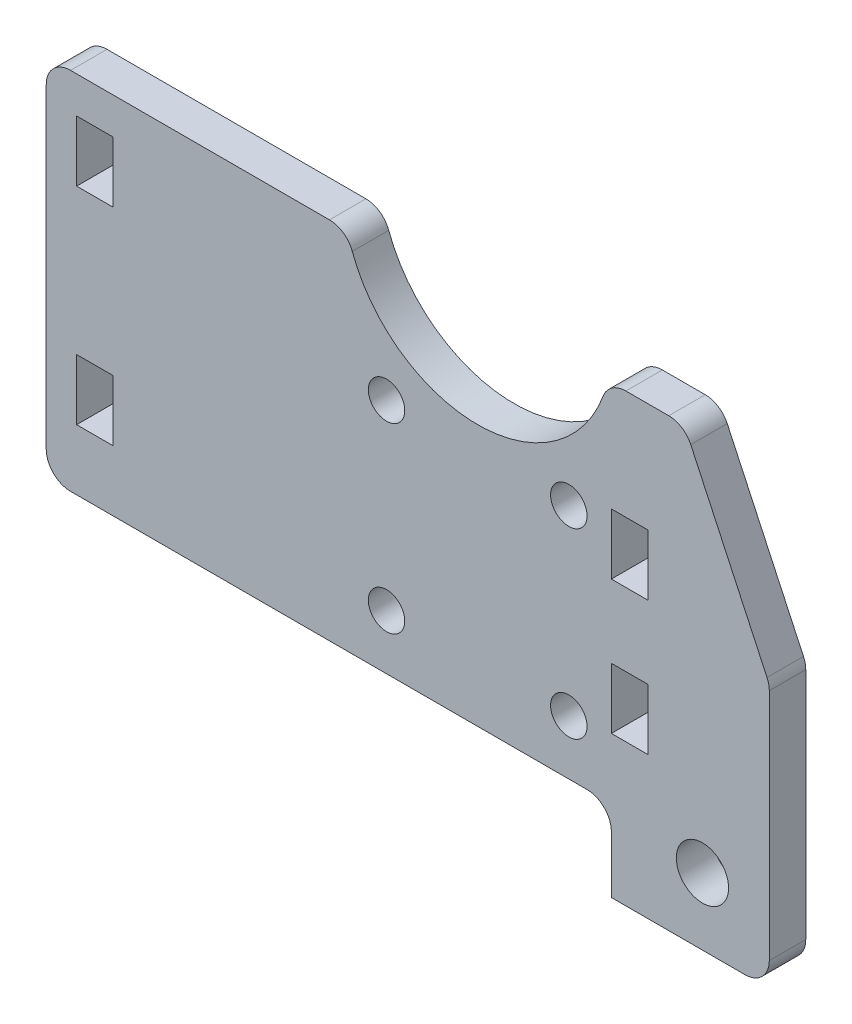
SolidWorks part; units mm, degrees
ref_plane "Front Plane" through (0, 0, 0) normal (0, 0, 1) x (1, 0, 0)
ref_plane "Top Plane" through (0, 0, 0) normal (0, 1, 0) x (1, 0, 0)
ref_plane "Right Plane" through (0, 0, 0) normal (1, 0, 0) x (0, 0, -1)
sketch "草图1" plane through (0, 0, 0) normal (0, 0, 1) x (1, 0, 0)
  line L1 (-26, -15) -> (26, -15)
  line L2 (-26, -15) -> (-26, 15)
  line L3 (-26, 15) -> (26, 15)
  line L4 (26, -15) -> (26, 15)
  line L5 (-26, -15) -> (26, 15) construction
  line L6 (-26, 15) -> (26, -15) construction
  point P0 (0, 0)
  dimension "D1" = 30
  dimension "D2" = 52
extrude "凸台-拉伸1" add sketch "草图1" along normal blind 3
sketch "草图2" plane through (0, 0, 3) normal (0, 0, 1) x (1, 0, 0)
  line L0 (0, 23.231) -> (0, -23.2713) construction
  line L1 (23.5, 27.0014) -> (23.5, -24.4496) construction
  line L2 (26, -15) -> (26, 15) construction
  line L3 (-29.6284, 0) -> (37.0615, 0) construction
  line L4 (-26, -15) -> (26, -15) construction
  line L5 (23.5, -5) -> (20.5, -5)
  line L6 (23.5, -5) -> (23.5, -10)
  line L7 (23.5, -10) -> (20.5, -10)
  line L8 (20.5, -5) -> (20.5, -10)
  line L9 (23.5, -5) -> (20.5, -10) construction
  line L10 (23.5, -10) -> (20.5, -5) construction
  line L11 (23.5, 12) -> (20.5, 12)
  line L12 (23.5, 12) -> (23.5, 7)
  line L13 (23.5, 7) -> (20.5, 7)
  line L14 (20.5, 12) -> (20.5, 7)
  line L15 (23.5, 12) -> (20.5, 7) construction
  line L16 (23.5, 7) -> (20.5, 12) construction
  line L17 (-23.5, 7) -> (-20.5, 12) construction
  line L18 (-23.5, 12) -> (-20.5, 7) construction
  line L19 (-23.5, -10) -> (-20.5, -5) construction
  line L20 (-23.5, -5) -> (-20.5, -10) construction
  line L21 (-20.5, 12) -> (-20.5, 7)
  line L22 (-23.5, 7) -> (-20.5, 7)
  line L23 (-23.5, 12) -> (-23.5, 7)
  line L24 (-23.5, 12) -> (-20.5, 12)
  line L25 (-20.5, -5) -> (-20.5, -10)
  line L26 (-23.5, -10) -> (-20.5, -10)
  line L27 (-23.5, -5) -> (-23.5, -10)
  line L28 (-23.5, -5) -> (-20.5, -5)
  point P13 (22, -7.5)
  point P18 (22, 9.5)
  point P29 (-22, 9.5)
  point P30 (-22, -7.5)
  dimension "D1" = 2.5
  dimension "D2" = 3
  dimension "D3" = 3
  dimension "D4" = 5
  dimension "D5" = 5
  dimension "D6" = 12
  dimension "D7" = 5
extrude "切除-拉伸1" cut sketch "草图2" against normal blind 4
sketch "草图6" plane through (0, 0, 0) normal (0, 0, -1) x (-1, 0, 0)
  line L1 (-24.1777, 12.7083) -> (-19.5538, 12.7083)
  line L2 (-24.1777, 12.7083) -> (-24.1777, 6.3305)
  line L3 (-24.1777, 6.3305) -> (-19.5538, 6.3305)
  line L4 (-19.5538, 12.7083) -> (-19.5538, 6.3305)
  line L5 (-24.1777, 12.7083) -> (-19.5538, 6.3305) construction
  line L6 (-24.1777, 6.3305) -> (-19.5538, 12.7083) construction
  point P4 (-21.8658, 9.5194)
extrude "凸台-拉伸2" add sketch "草图6" against normal up to surface (3 mm away) up to face at (-22, -7.5, 3)
sketch "草图7" plane through (0, 0, 0) normal (0, 0, -1) x (-1, 0, 0)
  line L1 (-23.5, 1) -> (-20.5, 1)
  line L2 (-23.5, 1) -> (-23.5, 6)
  line L3 (-23.5, 6) -> (-20.5, 6)
  line L4 (-20.5, 1) -> (-20.5, 6)
  line L5 (-23.5, 1) -> (-20.5, 6) construction
  line L6 (-23.5, 6) -> (-20.5, 1) construction
  line L7 (-23.5, -5) -> (-23.5, -10) construction
  line L8 (-20.5, -5) -> (-23.5, -5) construction
  point P4 (-22, 3.5)
  dimension "D1" = 3
  dimension "D2" = 5
  dimension "D3" = 6
extrude "切除-拉伸4" cut sketch "草图7" against normal blind 10
sketch "草图8" plane through (0, 0, 3) normal (0, 0, 1) x (1, 0, 0)
  line L0 (26, -15) -> (26, 15) construction
  line L1 (-26, -15) -> (26, -15) construction
  line L2 (26, 15) -> (31.495, 15)
  line L3 (31.495, 15) -> (31.495, -21.695)
  line L4 (31.495, -21.695) -> (20.5, -21.695)
  line L5 (20.5, -21.695) -> (20.5, -15)
  line L6 (20.5, -5) -> (20.5, -10) construction
  line L7 (26, 15) -> (26, -15)
  line L8 (26, -15) -> (20.5, -15)
  circle A0 centre (27.995, -16.195) radius 2
  dimension "D1" = 4
  dimension "D2" = 1.995
  dimension "D3" = 1.195
  dimension "D4" = 3.5
  dimension "5.5" = 5.5
extrude "凸台-拉伸3" add sketch "草图8" against normal up to surface (3 mm away) up to face at (22, 3.5, 0)
sketch "草图9" plane through (0, 0, 3) normal (0, 0, 1) x (1, 0, 0)
  circle A0 centre (27.995, -16.195) radius 2.25
  dimension "D1" = 4.5
extrude "切除-拉伸5" cut sketch "草图9" against normal blind 10
sketch "草图10" plane through (0, 0, 0) normal (0, 0, -1) x (-1, 0, 0)
  line L0 (-17, 4.5) -> (-2, 4.5) construction
  line L1 (-20.5, -10) -> (-20.5, -5) construction
  line L2 (26, -15) -> (-20.5, -15) construction
  line L3 (-17, 4.5) -> (-17, -10.5) construction
  circle A0 centre (-17, 4.5) radius 1.5
  circle A1 centre (-2, 4.5) radius 1.5
  circle A2 centre (-17, -10.5) radius 1.5
  circle A3 centre (-2, -10.5) radius 1.5
  dimension "D1" = 3
  dimension "D2" = 3
  dimension "D3" = 15
  dimension "D4" = 3
  dimension "D5" = 15
  dimension "D6" = 3
  dimension "D7" = 15
  dimension "D8" = 3.5
  dimension "D9" = 4.5
  dimension "D10" = 15
extrude "切除-拉伸6" cut sketch "草图10" against normal blind 10
sketch "草图11" plane through (0, 0, 0) normal (0, 0, -1) x (-1, 0, 0)
  line L1 (-17, 4.5) -> (-2, 4.5) construction
  line L2 (-9.5, 14.6303) -> (-9.5, -19.0429) construction
  circle A0 centre (-2, 4.5) radius 1.5 construction
  circle A1 centre (-17, 4.5) radius 1.5 construction
  circle A2 centre (-9.5, 17.5) radius 11
  dimension "D1" = 22
  dimension "D2" = 13
extrude "切除-拉伸7" cut sketch "草图11" against normal blind 10
fillet "圆角1" radius 2 2 edges at (20.2121, 15, 1.5) (20.5, -15, 1.5)
sketch "草图12" plane through (0, 0, 0) normal (0, 0, -1) x (-1, 0, 0)
  line L0 (-31.495, 15) -> (-33.495, 15)
  line L1 (-33.495, 15) -> (-33.495, -21.695)
  line L2 (-33.495, -21.695) -> (-31.495, -21.695)
  line L3 (-20.5, -21.695) -> (-31.495, -21.695) construction
  line L4 (-31.495, 15) -> (-31.495, -21.695)
  dimension "D1" = 2
extrude "凸台-拉伸4" add sketch "草图12" against normal up to surface (3 mm away) up to face at (0.5, 4.5, 3)
fillet "圆角2" radius 2 1 edges at (33.495, -21.695, 1.5)
chamfer "倒角1" distance 7 angle 65 1 edges at (33.495, 15, 1.5)
fillet "圆角3" radius 2 2 edges at (33.495, -0.0115, 1.5) (26.495, 15, 1.5)
sketch "草图13" plane through (0, 0, 0) normal (0, 0, -1) x (-1, 0, 0)
  circle A0 centre (-27.995, -16.195) radius 2.25
  circle A1 centre (-27.995, -16.195) radius 2.15
  dimension "D1" = 4.5
  dimension "D2" = 4.3
extrude "凸台-拉伸5" add sketch "草图13" against normal up to surface (3 mm away) up to face at (0.5, 4.5, 3)
fillet "圆角4" radius 2 2 edges at (-26, -15, 1.5) (-26, 15, 1.5)
